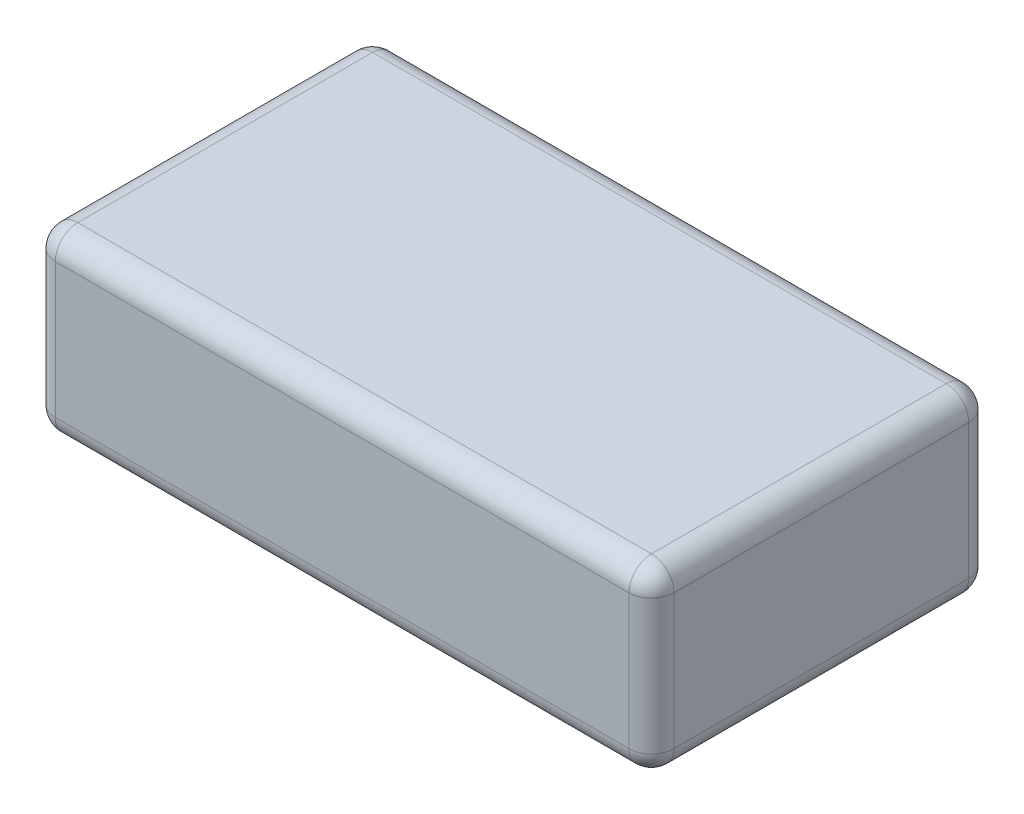
SolidWorks part; units mm, degrees
ref_plane "Front" through (0, 0, 0) normal (0, 0, 1) x (1, 0, 0)
ref_plane "Top" through (0, 0, 0) normal (0, 1, 0) x (1, 0, 0)
ref_plane "Right" through (0, 0, 0) normal (1, 0, 0) x (0, 0, -1)
sketch "Esboço1" plane through (0, 0, 0) normal (0, 1, 0) x (1, 0, 0)
  line L1 (-27.5, 15.1) -> (27.5, 15.1)
  line L2 (-27.5, 15.1) -> (-27.5, -15.1)
  line L3 (-27.5, -15.1) -> (27.5, -15.1)
  line L4 (27.5, 15.1) -> (27.5, -15.1)
  line L5 (-27.5, 15.1) -> (27.5, -15.1) construction
  line L6 (-27.5, -15.1) -> (27.5, 15.1) construction
  point P0 (0, 0)
  dimension "D1" = 55
  dimension "D2" = 30.2
extrude "Ressalto-extrusão1" add sketch "Esboço1" along normal blind 16
fillet "Filete1" radius 2 12 edges at (-27.5, 8, 15.1) (0, 16, 15.1) (-27.5, 16, 0) (0, 16, -15.1) (-27.5, 8, -15.1) (0, 0, -15.1) (-27.5, 0, 0) (0, 0, 15.1) (27.5, 8, 15.1) (27.5, 16, 0) (27.5, 8, -15.1) (27.5, 0, 0)
